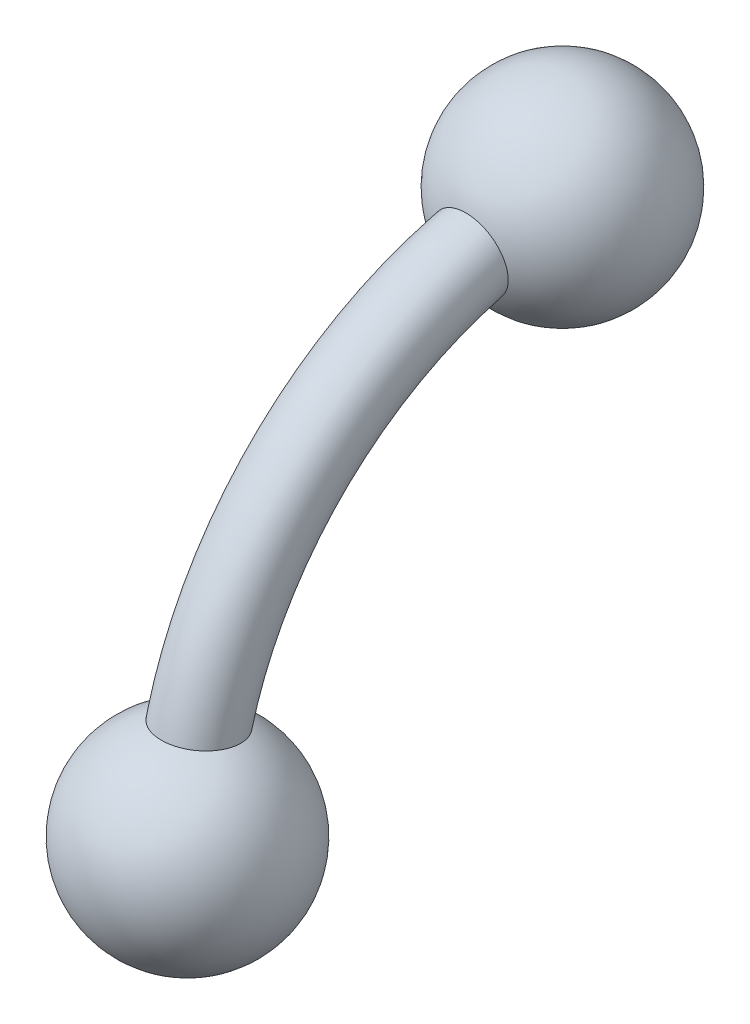
SolidWorks part; units mm, degrees
ref_plane "Plan de face" through (0, 0, 0) normal (0, 0, 1) x (1, 0, 0)
ref_plane "Plan de dessus" through (0, 0, 0) normal (0, 1, 0) x (1, 0, 0)
ref_plane "Plan de droite" through (0, 0, 0) normal (1, 0, 0) x (0, 0, -1)
sketch "Esquisse1" plane through (0, 0, 0) normal (0, 0, 1) x (1, 0, 0)
  line L0 (0, -4) -> (0, -3)
  line L1 (0, 3) -> (0, 4)
  line L2 (0, 3) -> (0, -3) construction
  arc A0 (0, 4) -> (0, -4) centre (0, 0) ccw
  arc A1 (0, 3) -> (0, -3) centre (0, 0) ccw
  dimension "D2" = 8
  dimension "D1" = 1
revolve "Révolution1" add sketch "Esquisse1" angle 360 about L0
sketch "Esquisse2" plane through (0, 0, 0) normal (0, 1, 0) x (1, 0, 0)
  line L0 (-4.7015, 15) -> (4.7015, 15) construction
  line L1 (0, 0) -> (0, 15) construction
  circle A0 centre (0, 0) radius 1.5
  circle A1 centre (0, 0) radius 1.25
  dimension "D1" = 3
  dimension "D3" = 2.5
  dimension "D2" = 15
revolve "Révolution2" add sketch "Esquisse2" angle 90 about L0
sketch "Esquisse3" plane through (0, 0, 0) normal (1, 0, 0) x (0, 0, -1)
  line L0 (15, 19) -> (15, 18)
  line L1 (15, 11) -> (15, 0) construction
  line L2 (0, 0) -> (15, 0) construction
  line L3 (15, 13.5) -> (15, 16.5) construction
  line L4 (15, 12) -> (15, 11)
  line L5 (15, 18) -> (15, 12) construction
  arc A0 (15, 19) -> (15, 11) centre (15, 15) ccw
  arc A1 (15, 18) -> (15, 12) centre (15, 15) ccw
  dimension "D1" = 8
  dimension "D2" = 1
revolve "Révolution3" add sketch "Esquisse3" angle 360 about L0
sketch "Esquisse4" plane through (0, 0, 0) normal (0, 1, 0) x (1, 0, 0)
  circle A0 centre (0, 0) radius 1.25
  dimension "D1" = 2.5
extrude "Enlèv. mat.-Extru.1" cut sketch "Esquisse4" against normal blind 10
ref_plane "Plan1" through (0, 0, -15) normal (0, 0, 1) x (1, 0, 0)
sketch "Esquisse5" plane through (0, 0, -15) normal (0, 0, 1) x (1, 0, 0)
  circle A0 centre (0, 15) radius 1.25
  circle A1 centre (0, 15) radius 4 construction
  dimension "D1" = 2.5
extrude "Enlèv. mat.-Extru.2" cut sketch "Esquisse5" against normal blind 10
